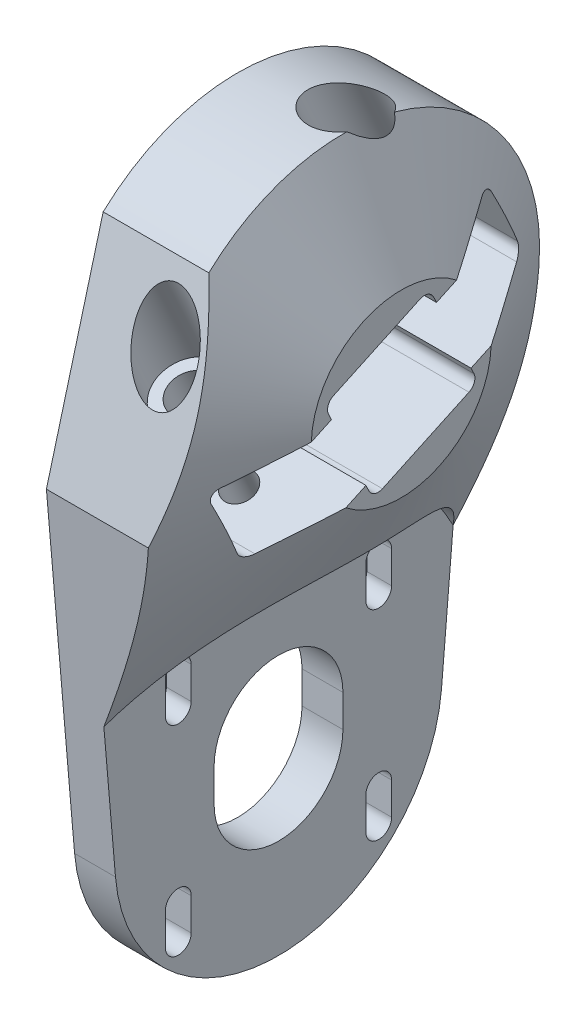
SolidWorks part; units mm, degrees
ref_plane "Front Plane" through (0, 0, 0) normal (0, 0, 1) x (1, 0, 0)
ref_plane "Top Plane" through (0, 0, 0) normal (0, 1, 0) x (1, 0, 0)
ref_plane "Right Plane" through (0, 0, 0) normal (1, 0, 0) x (0, 0, -1)
sketch "Sketch1" plane through (0, 0, 0) normal (1, 0, 0) x (0, 0, -1)
  line L0 (4.3532, 11.9603) -> (-11.9603, 4.3532)
  line L1 (4.3532, 11.9603) -> (11.9603, -4.3532)
  line L2 (-11.9603, 4.3532) -> (-4.3532, -11.9603)
  line L3 (11.9603, -4.3532) -> (-4.3532, -11.9603)
  line L4 (4.3532, 11.9603) -> (-4.3532, -11.9603) construction
  line L5 (-11.9603, 4.3532) -> (11.9603, -4.3532) construction
  line L6 (0, 0) -> (0, -57.15) construction
  line L7 (-30.3693, -2.5958) -> (-25.3077, -61.8132)
  line L8 (25.3077, -61.8132) -> (30.3693, -2.5958)
  line L9 (0, -57.15) -> (0, -103.9417) construction
  arc A0 (30.3693, -2.5958) -> (-30.3693, -2.5958) centre (0, 0) ccw
  arc A1 (-25.3077, -61.8132) -> (25.3077, -61.8132) centre (0, -59.65) ccw
  dimension "D1" = 2.5
  dimension "D2" = 30.48
  dimension "D6" = 57.15
  dimension "D7" = 25.4
  dimension "D8" = 0
  dimension "D3" = 18
  dimension "D4" = 18
  dimension "D5" = 25
extrude "Boss-Extrude1" add sketch "Sketch1" along normal blind 6.35
sketch "Sketch19" plane through (6.35, 0, 0) normal (1, 0, 0) x (0, 0, -1)
  line L0 (0, -59.65) -> (0, -54.65)
  line L1 (0, -54.65) -> (15.5563, -39.0937) construction
  line L2 (15.5563, -44.0937) -> (15.5563, -39.0937) construction
  line L3 (13.5563, -44.0937) -> (13.5563, -39.0937)
  line L4 (17.5563, -44.0937) -> (17.5563, -39.0937)
  line L5 (-10, -59.65) -> (-10, -54.65)
  line L6 (10, -59.65) -> (10, -54.65)
  line L7 (0, -57.15) -> (7.4061, -57.15) construction
  line L8 (15.5563, -44.0937) -> (0, -59.65) construction
  line L9 (17.5563, -70.2063) -> (17.5563, -75.2063)
  line L10 (13.5563, -70.2063) -> (13.5563, -75.2063)
  line L11 (-17.5563, -44.0937) -> (-17.5563, -39.0937)
  line L12 (-13.5563, -44.0937) -> (-13.5563, -39.0937)
  line L13 (-13.5563, -70.2063) -> (-13.5563, -75.2063)
  line L14 (-17.5563, -70.2063) -> (-17.5563, -75.2063)
  line L15 (-15.5563, -44.0937) -> (0, -59.65) construction
  line L16 (0, -59.65) -> (-15.5563, -75.2063) construction
  line L17 (0, -59.65) -> (15.5563, -75.2063) construction
  arc A0 (-25.3077, -61.8132) -> (25.3077, -61.8132) centre (0, -59.65) ccw construction
  arc A1 (-25.3077, -61.8132) -> (25.3077, -61.8132) centre (0, -59.65) ccw
  arc A2 (-10, -59.65) -> (10, -59.65) centre (0, -59.65) ccw
  arc A3 (17.5563, -75.2063) -> (13.5563, -75.2063) centre (15.5563, -75.2063) cw
  arc A4 (13.5563, -70.2063) -> (17.5563, -70.2063) centre (15.5563, -70.2063) cw
  arc A6 (17.5563, -39.0937) -> (13.5563, -39.0937) centre (15.5563, -39.0937) ccw
  arc A7 (13.5563, -44.0937) -> (17.5563, -44.0937) centre (15.5563, -44.0937) ccw
  arc A8 (-17.5563, -39.0937) -> (-13.5563, -39.0937) centre (-15.5563, -39.0937) cw
  arc A9 (10, -54.65) -> (-10, -54.65) centre (0, -54.65) ccw
  arc A10 (-13.5563, -44.0937) -> (-17.5563, -44.0937) centre (-15.5563, -44.0937) cw
  arc A11 (-13.5563, -70.2063) -> (-17.5563, -70.2063) centre (-15.5563, -70.2063) ccw
  arc A13 (-17.5563, -75.2063) -> (-13.5563, -75.2063) centre (-15.5563, -75.2063) ccw
  point P8 (0, -57.15)
  dimension "D1" = 135
  dimension "D3" = 22
  dimension "D5" = 4
  dimension "D6" = 5
  dimension "D4" = 4
  dimension "D8" = 0
  dimension "D2" = 5
  dimension "D7" = 45
extrude "Cut-Extrude18" cut sketch "Sketch19" against normal blind 10
sketch "Sketch20" plane through (6.35, 0, 0) normal (1, 0, 0) x (0, 0, -1)
  circle A0 centre (0, 0) radius 57.15
  arc A1 (-25.3077, -61.8132) -> (25.3077, -61.8132) centre (0, -59.65) ccw construction
  point P3 (0, -85.05)
extrude "Boss-Extrude5" add sketch "Sketch20" along normal blind 19.05
sketch "Sketch21" plane through (0, 0, 0) normal (-1, 0, 0) x (0, 0, 1)
  line L0 (-24.435, 4.3878) -> (-10.8404, -1.9515)
  line L1 (11.9603, 4.3532) -> (4.3532, -11.9603) construction
  line L3 (-4.3532, 11.9603) -> (-11.9603, -4.3532) construction
  line L4 (-4.3532, 11.9603) -> (11.9603, 4.3532) construction
  line L5 (11.9603, 4.3532) -> (10.8404, 1.9515)
  line L7 (-4.3532, 11.9603) -> (-5.4731, 9.5586)
  line L8 (-4.3532, 11.9603) -> (11.9603, 4.3532)
  line L9 (-21.7514, 10.1428) -> (-25.3766, 11.8333) construction
  line L10 (19.0678, -15.8979) -> (5.4731, -9.5586)
  line L11 (19.0678, -15.8979) -> (24.435, -4.3878)
  line L12 (-24.435, 4.3878) -> (-19.0678, 15.8979)
  line L13 (24.435, -4.3878) -> (10.8404, 1.9515)
  line L16 (4.3532, -11.9603) -> (5.4731, -9.5586)
  line L17 (-11.9603, -4.3532) -> (-10.8404, -1.9515)
  line L18 (11.9603, 4.3532) -> (-4.3532, 11.9603)
  line L21 (-10.8404, -1.9515) -> (-11.9603, -4.3532)
  line L24 (-10.8404, -1.9515) -> (-24.435, 4.3878)
  line L27 (-5.4731, 9.5586) -> (-4.3532, 11.9603)
  line L29 (-5.4731, 9.5586) -> (-19.0678, 15.8979)
  line L30 (5.4731, -9.5586) -> (4.3532, -11.9603)
  line L31 (10.8404, 1.9515) -> (11.9603, 4.3532)
  line M13 (-11.9603, -4.3532) -> (-4.3532, 11.9603)
  line M14 (-4.3532, 11.9603) -> (11.9603, 4.3532)
  line M15 (11.9603, 4.3532) -> (4.3532, -11.9603)
  line M16 (4.3532, -11.9603) -> (-11.9603, -4.3532)
  dimension "D1" = 15
  dimension "D2" = 12.7
extrude "Cut-Extrude14" cut sketch "Sketch21" against normal through all contours L29 L12 L0 M13 | M13 M16 M15 M14 | L11 L13 L10 M15
sketch "Sketch22" plane through (0, 5.7551, 2.6836) normal (0, -0.9063, -0.4226) x (-1, 0, 0)
  line L0 (-25.4, -9) -> (0, -9) construction
  line L2 (0, -28.6209) -> (0, 30.48) construction
  circle A0 centre (-12.5, -16.5) radius 3.175
  dimension "D2" = 12.5
  dimension "D3" = 6.35
  dimension "D1" = 7.5
extrude "Cut-Extrude15" cut sketch "Sketch22" against normal through all
ref_plane "Plane1" through (0, 10.3591, 4.8305) normal (0, -0.9063, -0.4226) x (-1, 0, 0)
sketch "Sketch24" plane through (0, 10.3591, 4.8305) normal (0, -0.9063, -0.4226) x (-1, 0, 0)
  circle A0 centre (-12.5, -16.5) radius 5
  dimension "D1" = 10
extrude "Cut-Extrude16" cut sketch "Sketch24" against normal through all
sketch "Sketch25" plane through (0, -5.7551, -2.6836) normal (0, 0.9063, 0.4226) x (1, 0, 0)
  circle A0 centre (12.5, -16.5) radius 3.175 construction
  circle A1 centre (12.5, -16.5) radius 3.175
  circle A2 centre (12.5, -16.5) radius 2.3813
  dimension "D1" = 0.7937
extrude "Cut-Extrude17" cut sketch "Sketch25" against normal blind 10 contours A2
ref_plane "Plane2" through (0, 0, 0) normal (0, 0.4226, -0.9063) x (-1, 0, 0)
mirror "Mirror1" about plane through (0, 0, 0) normal (0, 0.4226, -0.9063) of "Cut-Extrude17", "Cut-Extrude15", "Cut-Extrude16"
mirror "Mirror2" about plane through (0, 0, 0) normal (1, 0, 0) of bodies 124 126
delete or keep bodies "Body-Delete/Keep 1" type delete bodies bodies 127
chamfer "Chamfer2" distance 2.5 angle 45 8 edges at (0, -46.0937, 15.5563) (0, -41.5937, 13.5563) (0, -37.0937, 15.5563) (0, -41.5937, 17.5563) (0, -46.0937, -15.5563) (0, -41.5937, -17.5563) (0, -41.5937, -13.5563) (0, -37.0937, -15.5563)
sketch "Sketch26" plane through (0, 0, 0) normal (-1, 0, 0) x (0, 0, 1)
  line L0 (11.4538, -58.2291) -> (27.0119, -8.4408)
  line L1 (0, 0) -> (0, -54.65) construction
  circle A0 centre (0, -54.65) radius 12
  circle A1 centre (0, 0) radius 28.3
  dimension "D1" = 24
  dimension "D2" = 56.6
fillet "Fillet1" radius 1.5875 8 edges at (12.7, 4.3878, -24.435) (12.7, 15.8979, -19.0678) (12.7, -4.3878, 24.435) (12.7, -15.8979, 19.0678) (12.7, 11.9603, -4.3532) (12.7, 4.3532, 11.9603) (12.7, -11.9603, 4.3532) (12.7, -4.3532, -11.9603)
sketch "Sketch28" plane through (6.35, 0, 0) normal (1, 0, 0) x (0, 0, -1)
  arc A0 (-10, -54.65) -> (10, -54.65) centre (0, -54.65) ccw construction
  arc A1 (-10, -54.65) -> (10, -54.65) centre (0, -54.65) ccw
  circle A3 centre (0, -54.65) radius 30.48
extrude "Cut-Extrude19" cut sketch "Sketch28" along normal through all contours A3
sketch "Sketch29" plane through (25.4, 0, 0) normal (1, 0, 0) x (0, 0, -1)
  arc A1 (30.3693, -2.5958) -> (-30.3693, -2.5958) centre (0, 0) ccw construction
  arc A2 (30.3693, -2.5958) -> (-30.3693, -2.5958) centre (0, 0) ccw
  circle A3 centre (0, 0) radius 13.97
sketch "Sketch30" plane through (6.35, 0, 0) normal (1, 0, 0) x (0, 0, -1)
  circle A0 centre (0, 0) radius 48.9194
sketch "Sketch31" plane through (0, 0, 0) normal (0, 1, 0) x (1, 0, 0)
  line L0 (25.4, -13.97) -> (25.4, 13.97) construction
  line L1 (25.4, -13.97) -> (25.4, 13.97)
  line L2 (6.35, -48.9194) -> (6.35, 48.9194) construction
  line L3 (6.35, -48.9194) -> (6.35, 48.9194)
  line L4 (25.4, -13.97) -> (6.35, -48.9194)
  line L5 (6.35, -48.9194) -> (6.35, -59.9521)
  line L6 (6.35, -59.9521) -> (25.4, -59.9521)
  line L7 (25.4, -59.9521) -> (25.4, -13.97)
  line L8 (25.4, 0) -> (0, 0) construction
revolve "Cut-Revolve1" cut sketch "Sketch31" angle 360 about L8
sketch "Sketch32" plane through (6.35, 0, 0) normal (-1, 0, 0) x (0, 0, 1)
  line L0 (30.3693, -2.5958) -> (25.3077, -61.8132) construction
  line L1 (-25.3077, -61.8132) -> (-30.3693, -2.5958) construction
  line L2 (30.3693, -2.5958) -> (25.3077, -61.8132)
  line L3 (-25.3077, -61.8132) -> (-30.3693, -2.5958)
  arc A0 (30.3693, -2.5958) -> (-30.3693, -2.5958) centre (0, 0) ccw construction
  arc A1 (30.3693, -2.5958) -> (-30.3693, -2.5958) centre (0, 0) ccw
  circle A2 centre (0, 0) radius 48.9194 construction
  circle A3 centre (0, 0) radius 48.9194
  arc M2 (27.1106, -40.72) -> (-27.1106, -40.72) centre (0, 0) ccw
  line M3 (-27.1106, -40.72) -> (-30.3693, -2.5958)
  arc M4 (-30.3693, -2.5958) -> (30.3693, -2.5958) centre (0, 0) cw
  line M5 (30.3693, -2.5958) -> (27.1106, -40.72)
extrude "Cut-Extrude20" cut sketch "Sketch32" against normal through all contours M5 M2 M3 M4
sketch "Sketch33" plane through (0, 0, 0) normal (-1, 0, 0) x (0, 0, 1)
  line L0 (30.3693, -2.5958) -> (25.3077, -61.8132) construction
  line L1 (30.3693, -2.5958) -> (25.3077, -61.8132)
  line L2 (29.6796, -10.6648) -> (20.8695, 22.2147)
  line L3 (22.9962, -3.7169) -> (10.8404, 1.9515) construction
  arc A0 (30.3693, -2.5958) -> (-30.3693, -2.5958) centre (0, 0) ccw construction
  arc A1 (30.3693, -2.5958) -> (-30.3693, -2.5958) centre (0, 0) ccw
  arc M35 (30.3693, -2.5958) -> (-30.3693, -2.5958) centre (0, 0) ccw
  dimension "D1" = 50
  dimension "D2" = 25.908
extrude "Cut-Extrude21" cut sketch "Sketch33" against normal through all contours L2 L1 M35
equation "\".75i\"=14.27"
